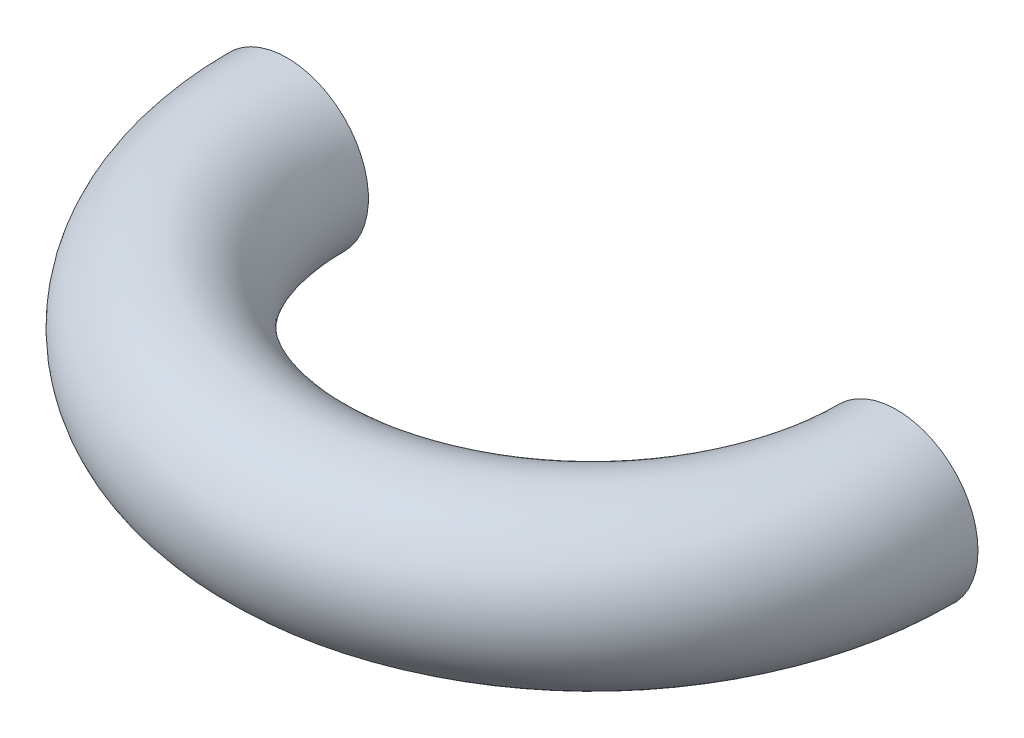
SolidWorks part; units mm, degrees
ref_plane "Спереди" through (0, 0, 0) normal (0, 0, 1) x (1, 0, 0)
ref_plane "Сверху" through (0, 0, 0) normal (0, 1, 0) x (1, 0, 0)
ref_plane "Справа" through (0, 0, 0) normal (1, 0, 0) x (0, 0, -1)
sketch "Эскиз1" plane through (0, 0, 0) normal (0, 0, 1) x (1, 0, 0)
  line L0 (0, 7.8754) -> (0, -5.8945) construction
  circle A0 centre (3.75, 0) radius 1
  dimension "D1" = 2
  dimension "D2" = 3.75
revolve "Повернуть1" add sketch "Эскиз1" angle 180 about L0
